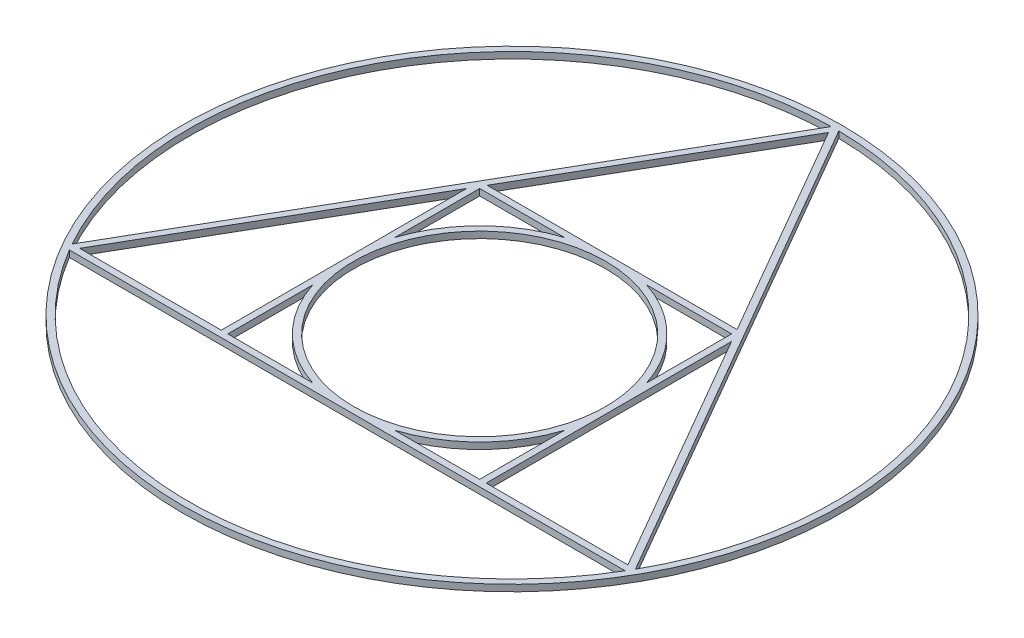
SolidWorks part; units mm, degrees
ref_plane "Front Plane" through (0, 0, 0) normal (0, 0, 1) x (1, 0, 0)
ref_plane "Top Plane" through (0, 0, 0) normal (0, 1, 0) x (1, 0, 0)
ref_plane "Right Plane" through (0, 0, 0) normal (1, 0, 0) x (0, 0, -1)
sketch "Sketch1" plane through (0, 0, 0) normal (0, 1, 0) x (1, 0, 0)
  line L0 (73.4335, -87.7425) -> (151.9745, -87.7425)
  line L41 (-2.0913, 179.0828) -> (-156.1359, -87.7303)
  line L42 (-154.0446, -91.3525) -> (154.0446, -91.3525)
  line L43 (156.1359, -87.7303) -> (2.0913, 179.0828)
  line L44 (0, 175.485) -> (-69.265, 55.5145)
  line L45 (-151.9745, -87.7425) -> (-73.4335, -87.7425)
  line L46 (151.9745, -87.7425) -> (73.4335, 48.2945)
  line L47 (73.4335, -91.3525) -> (-73.4335, -91.3525)
  line L48 (73.4335, -87.7425) -> (73.4335, 48.2945)
  line L50 (-73.4335, -87.7425) -> (-73.4335, 48.2945)
  line L51 (69.8235, -87.7425) -> (22.7411, -87.7425)
  line L52 (69.8235, -87.7425) -> (69.8235, -40.6601)
  line L53 (69.8235, 51.9045) -> (22.7411, 51.9045)
  line L54 (-69.8235, -87.7425) -> (-69.8235, -40.6601)
  line L55 (-69.8235, -87.7425) -> (-22.7411, -87.7425)
  line L56 (-22.7411, -87.7425) -> (-69.8235, -87.7425)
  line L57 (22.7411, -87.7425) -> (69.8235, -87.7425)
  line L58 (69.8235, 4.8221) -> (69.8235, 51.9045)
  line L59 (69.265, 55.5145) -> (0, 175.485)
  line L60 (-22.7411, 51.9045) -> (-69.8235, 51.9045)
  line L61 (69.265, 55.5145) -> (-69.265, 55.5145)
  line L62 (-73.4335, 48.2945) -> (-151.9745, -87.7425)
  line L63 (-69.8235, 4.8221) -> (-69.8235, 51.9045)
  arc A0 (-2.0913, 179.0828) -> (-156.1359, -87.7303) centre (0, 0) ccw
  circle A1 centre (0, 0) radius 182.705
  arc A6 (22.7411, -87.7425) -> (69.8235, -40.6601) centre (0, -17.919) ccw
  circle A7 centre (0, -17.919) radius 69.8235
  arc A8 (-154.0446, -91.3525) -> (154.0446, -91.3525) centre (0, 0) ccw
  arc A9 (156.1359, -87.7303) -> (2.0913, 179.0828) centre (0, 0) ccw
  arc A10 (69.8235, 4.8221) -> (22.7411, 51.9045) centre (0, -17.919) ccw
  arc A11 (-22.7411, 51.9045) -> (-69.8235, 4.8221) centre (0, -17.919) ccw
  arc A12 (-69.8235, -40.6601) -> (-22.7411, -87.7425) centre (0, -17.919) ccw
  point P23 (151.9745, -87.7425)
  dimension "D1" = 358.19
  dimension "D2" = 365.41
  dimension "D7" = 3.61
  dimension "D3" = 3.61
  dimension "D4" = 3.61
  dimension "D6" = 3.61
extrude "Boss-Extrude4" add sketch "Sketch1" along normal blind 3.61 contours A1 A9 L43 A8 L42 A7 L59 L61 L44 L0 L48 L46 L62 L50 L45 A0 L41 L51 A6 L52 L58 A10 L53 L60 A11 L63 L54 A12 L55
